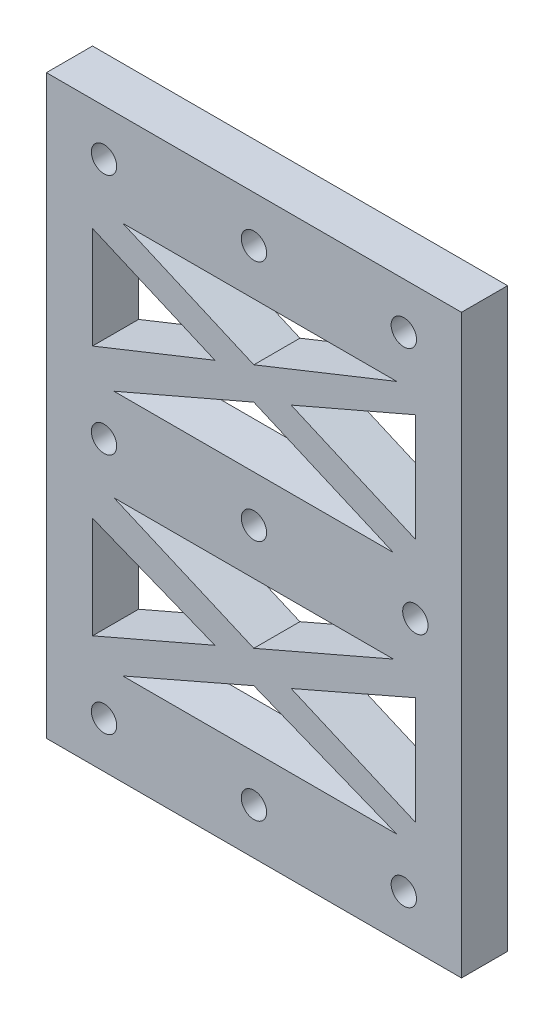
SolidWorks part; units mm, degrees
ref_plane "前视基准面" through (0, 0, 0) normal (0, 0, 1) x (1, 0, 0)
ref_plane "上视基准面" through (0, 0, 0) normal (0, 1, 0) x (1, 0, 0)
ref_plane "右视基准面" through (0, 0, 0) normal (1, 0, 0) x (0, 0, -1)
sketch "草图1" plane through (0, 0, 0) normal (0, 0, 1) x (1, 0, 0)
  line L1 (-36, 50) -> (36, 50)
  line L2 (-36, 50) -> (-36, -50)
  line L3 (-36, -50) -> (36, -50)
  line L4 (36, 50) -> (36, -50)
  line L5 (-36, 50) -> (36, -50) construction
  line L6 (-36, -50) -> (36, 50) construction
  point P0 (0, 0)
  dimension "D1" = 100
  dimension "D2" = 72
extrude "凸台-拉伸1" add sketch "草图1" along normal blind 8
sketch "草图2" plane through (0, 0, 8) normal (0, 0, 1) x (1, 0, 0)
  line L0 (36, -50) -> (36, 50) construction
  line L1 (-28, 34) -> (28, 34)
  line L2 (-28, 34) -> (-28, 8)
  line L3 (-28, 8) -> (28, 8)
  line L4 (28, 34) -> (28, 8)
  line L5 (-28, -8) -> (28, -8)
  line L6 (-28, -8) -> (-28, -34)
  line L7 (-28, -34) -> (28, -34)
  line L8 (28, -8) -> (28, -34)
  line L9 (-36, 50) -> (-36, -50) construction
  line L10 (0, 50) -> (0, -50) construction
  line L11 (36, 50) -> (-36, 50) construction
  line L12 (-36, -50) -> (36, -50) construction
  line L13 (-36, 0) -> (36, 0) construction
  circle A0 centre (-26, -42) radius 2.2
  circle A1 centre (0, -42) radius 2.2
  circle A2 centre (26, -42) radius 2.2
  circle A3 centre (26, 42) radius 2.2
  circle A4 centre (0, 42) radius 2.2
  circle A5 centre (-26, 42) radius 2.2
  circle A6 centre (-26, 0) radius 2.2
  circle A7 centre (0, 0) radius 2.2
  circle A8 centre (28, 0) radius 2.2
  dimension "D6" = 4.4
  dimension "D7" = 4.4
  dimension "D8" = 4.4
  dimension "D9" = 4.4
  dimension "D10" = 4.4
  dimension "D11" = 4.4
  dimension "D1" = 8
  dimension "D2" = 8
  dimension "D3" = 8
  dimension "D4" = 26
  dimension "D5" = 26
  dimension "D12" = 8
  dimension "D13" = 8
  dimension "D14" = 8
  dimension "D15" = 8
  dimension "D16" = 8
  dimension "D17" = 8
extrude "切除-拉伸1" cut sketch "草图2" against normal up to next
sketch "草图3" plane through (0, 0, 8) normal (0, 0, 1) x (1, 0, 0)
  line L0 (-28, 30.6012) -> (-6.7687, 21.4072)
  line L1 (-28, 34) -> (-28, 8) construction
  line L2 (-28, 8) -> (28, 8) construction
  line L3 (-22.7461, 34) -> (-0.0166, 24.1027)
  line L4 (28, 34) -> (-28, 34) construction
  line L5 (28, 8) -> (28, 34) construction
  line L7 (-24.2882, 8) -> (-0.0258, 18.4873)
  line L8 (-28, 30.6012) -> (-28, 34)
  line L9 (-28, 34) -> (-22.7461, 34)
  line L11 (28, 34) -> (28, 30.6012)
  line L12 (28, 11.9032) -> (28, 8)
  line L13 (28, 8) -> (24.1918, 8)
  line L15 (-28, 8) -> (-24.2882, 8)
  line L16 (0, 50) -> (0, 24.1093) construction
  line L17 (36, 50) -> (-36, 50) construction
  line L18 (-36, -50) -> (36, -50) construction
  line L22 (24.7762, 34) -> (-0.0166, 24.1027)
  line L24 (24.7762, 34) -> (28, 34)
  line L25 (6.4506, 21.2866) -> (28, 11.9032)
  line L26 (-6.7687, 21.4072) -> (-28, 12.9316)
  line L27 (-0.0258, 18.4873) -> (24.1918, 8)
  line L28 (6.4506, 21.2866) -> (28, 30.6012)
  line L29 (-28, 12.9316) -> (-28, 8)
  line L30 (0, 18.4761) -> (0, -50) construction
  line L31 (-36, 0) -> (36, 0) construction
  line L32 (-36, 50) -> (-36, -50) construction
  line L33 (36, -50) -> (36, 50) construction
  line L34 (-28, -8) -> (-24.2882, -8)
  line L35 (-28, -12.9316) -> (-28, -8)
  line L36 (-6.7687, -21.4072) -> (-28, -12.9316)
  line L37 (-28, -30.6012) -> (-6.7687, -21.4072)
  line L38 (-28, -30.6012) -> (-28, -34)
  line L39 (-28, -34) -> (-22.7461, -34)
  line L40 (-22.7461, -34) -> (-0.0166, -24.1027)
  line L41 (24.7762, -34) -> (-0.0166, -24.1027)
  line L42 (24.7762, -34) -> (28, -34)
  line L43 (28, -34) -> (28, -30.6012)
  line L44 (6.4506, -21.2866) -> (28, -30.6012)
  line L45 (6.4506, -21.2866) -> (28, -11.9032)
  line L46 (28, -11.9032) -> (28, -8)
  line L47 (28, -8) -> (24.1918, -8)
  line L48 (-0.0258, -18.4873) -> (24.1918, -8)
  line L49 (-24.2882, -8) -> (-0.0258, -18.4873)
extrude "凸台-拉伸2" add sketch "草图3" against normal blind 8
